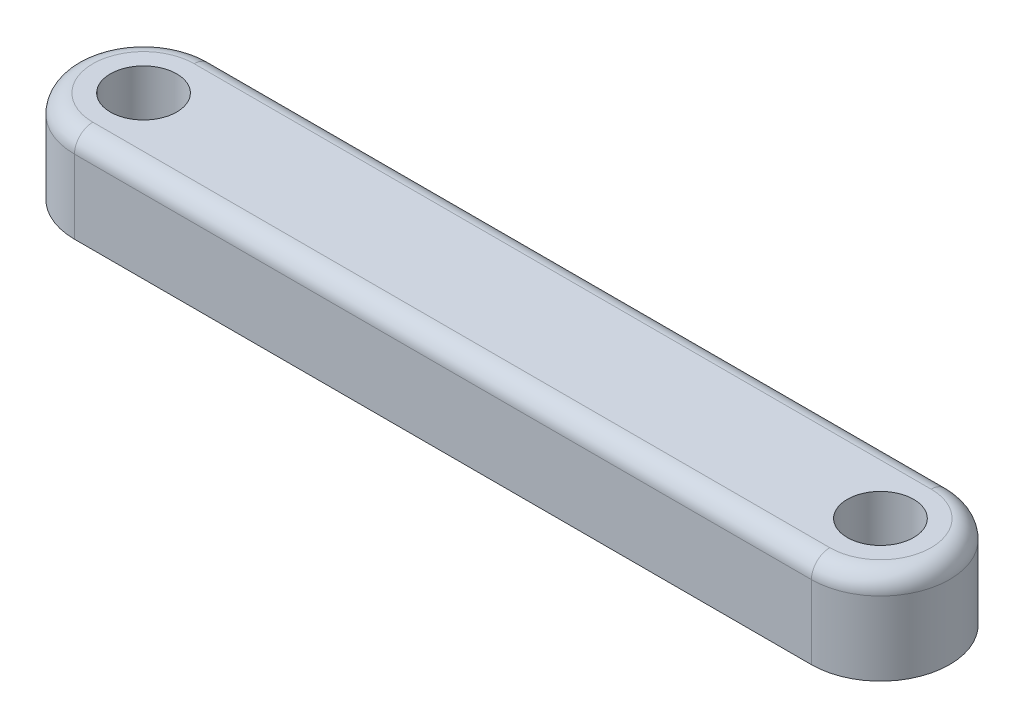
SolidWorks part; units mm, degrees
ref_plane "Front Plane" through (0, 0, 0) normal (0, 0, 1) x (1, 0, 0)
ref_plane "Top Plane" through (0, 0, 0) normal (0, 1, 0) x (1, 0, 0)
ref_plane "Right Plane" through (0, 0, 0) normal (1, 0, 0) x (0, 0, -1)
sketch "Sketch1" plane through (0, 0, 0) normal (0, 1, 0) x (1, 0, 0)
  line L0 (0, 0) -> (-50.8, 0) construction
  line L1 (0, -4.7625) -> (-50.8, -4.7625)
  line L2 (0, 4.7625) -> (-50.8, 4.7625)
  arc A0 (0, -4.7625) -> (0, 4.7625) centre (0, 0) ccw
  arc A1 (-50.8, 4.7625) -> (-50.8, -4.7625) centre (-50.8, 0) ccw
  circle A2 centre (-50.8, 0) radius 2.286
  circle A3 centre (0, 0) radius 2.286
  point P3 (-25.4, 0)
  dimension "D1" = 4.572
  dimension "D2" = 4.7625
  dimension "D3" = 50.8
extrude "Boss-Extrude1" add sketch "Sketch1" along normal blind 6.35
fillet "Fillet1" radius 1.27 4 edges at (4.7625, 6.35, 0) (-25.4, 6.35, 4.7625) (-55.5625, 6.35, 0) (-25.4, 6.35, -4.7625)
